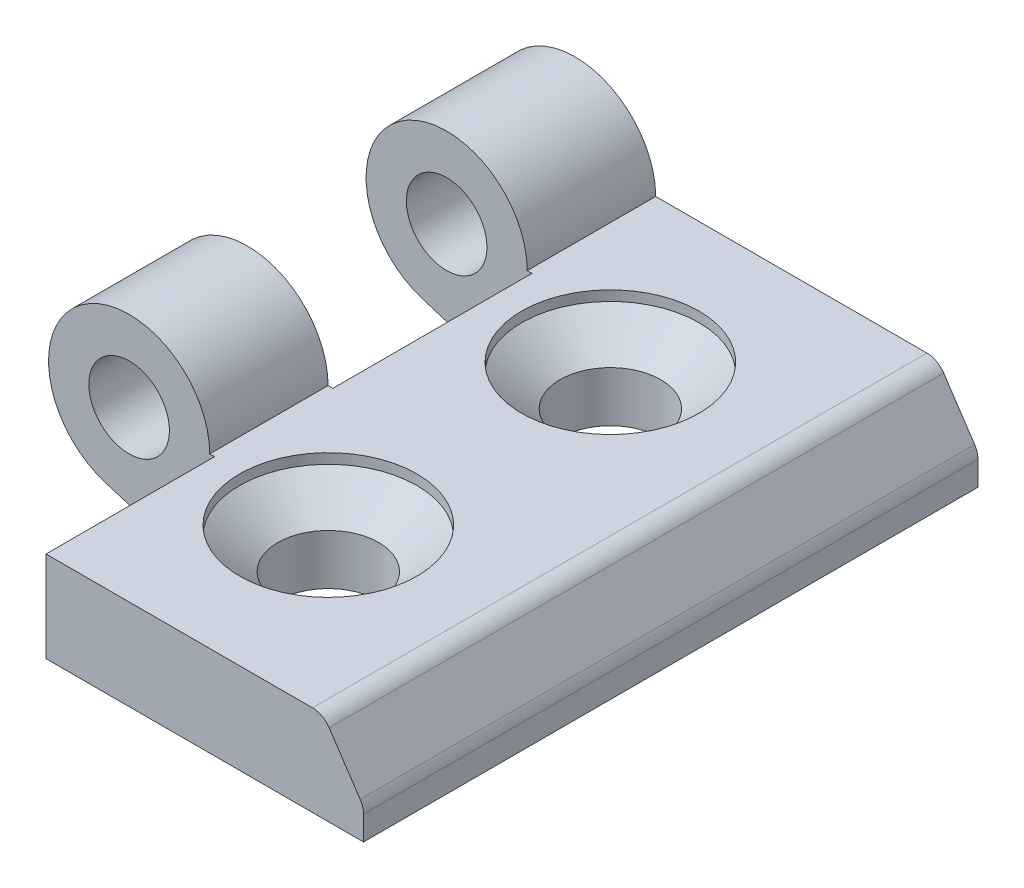
SolidWorks part; units mm, degrees
ref_plane "前视基准面" through (0, 0, 0) normal (0, 0, 1) x (1, 0, 0)
ref_plane "上视基准面" through (0, 0, 0) normal (0, 1, 0) x (1, 0, 0)
ref_plane "右视基准面" through (0, 0, 0) normal (1, 0, 0) x (0, 0, -1)
sketch "草图1" plane through (0, 0, 0) normal (0, 0, 1) x (1, 0, 0)
  line B0 (20, -4.5) -> (1, -4.5)
  line B1 (20, -3.3028) -> (20, -4.5)
  line B2 (20, -4.5) -> (1, -4.5)
  line B3 (17.4648, 0) -> (4, 0)
  line B4 (19.8321, -2.7481) -> (18.2969, -0.4453)
  line B5 (1, -4.5) -> (-1.1879, -3.8195)
  arc B6 (20, -3.3028) -> (19.8321, -2.7481) centre (19, -3.3028) ccw
  arc B7 (18.2969, -0.4453) -> (17.4648, 0) centre (17.4648, -1) ccw
  arc B8 (4, 0) -> (-1.1879, -3.8195) centre (0, 0) ccw
sketch_block_instance "A$C03935E30-1"
sketch_block "A$C03935E30"
extrude "凸台-拉伸1" add sketch "草图1" along normal mid plane 30.5 contours B3 B8 B5 B0 B1 B6 B4 B7
sketch "草图3" plane through (0, 0, 0) normal (0, 1, 0) x (1, 0, 0)
  line L1 (-4, -15.25) -> (4.2382, -15.25)
  line L2 (-4, -15.25) -> (-4, -6.885)
  line L3 (-4, -6.885) -> (4.2382, -6.885)
  line L4 (4.2382, -15.25) -> (4.2382, -6.885)
  line L5 (-4, -0.51) -> (4, -0.51) construction
  line L6 (4, 8.375) -> (-4, 8.375) construction
  line L7 (4, -7.385) -> (-4, -7.385) construction
  line L8 (-4, -1.01) -> (4.2382, -1.01)
  line L9 (-4, -1.01) -> (-4, 8.875)
  line L10 (-4, 8.875) -> (4.2382, 8.875)
  line L11 (4.2382, -1.01) -> (4.2382, 8.875)
  dimension "D1" = 0.5
  dimension "D2" = 0.5
  dimension "D3" = 0.5
extrude "切除-拉伸1" cut sketch "草图3" against normal through all and the other way through all
sketch "草图4" plane through (0, 0, 6.885) normal (0, 0, 1) x (1, 0, 0)
  circle A0 centre (0, 0) radius 2
extrude "切除-拉伸2" cut sketch "草图4" against normal through all
ref_plane "基准面2" through (0, 0, 7) normal (0, 0, 1) x (1, 0, 0)
sketch "草图5" plane through (0, 0, 7) normal (0, 0, 1) x (1, 0, 0)
  line L0 (10, -4.5) -> (10, 0)
  line L1 (20, -4.5) -> (4.2382, -4.5) construction
  line L2 (17.4648, 0) -> (4.2382, 0) construction
  line L3 (10, 0) -> (14.4, 0)
  line L4 (10, -4.5) -> (12.5, -4.5)
  line L5 (14.4, 0) -> (14.4, -0.5)
  line L6 (12.5, -4.5) -> (12.5, -2)
  line L7 (12.5, -2) -> (14.4, -0.5)
  circle A0 centre (0, 0) radius 2 construction
  dimension "D1" = 10
revolve "切除-旋转1" cut sketch "草图5" angle 360 about L0
pattern_linear "阵列(线性)1" count 2 spacing 14 along (0, 0, -1) of "切除-旋转1"
